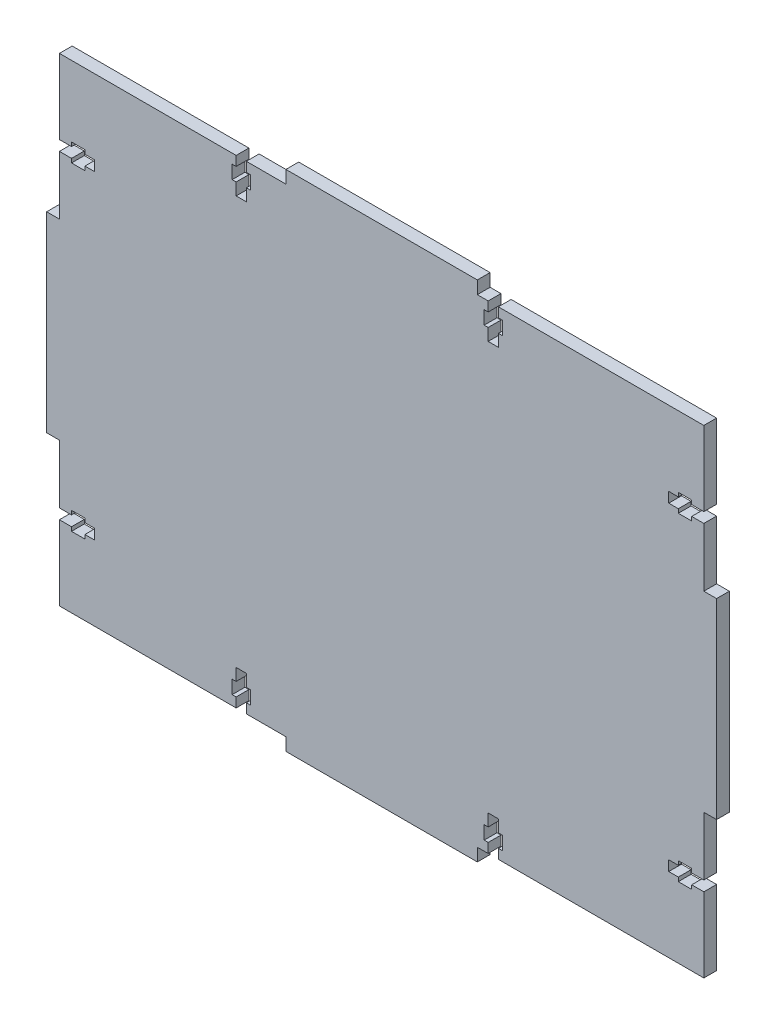
SolidWorks part; units mm, degrees
ref_plane "Plan de face" through (0, 0, 0) normal (0, 0, 1) x (1, 0, 0)
ref_plane "Plan de dessus" through (0, 0, 0) normal (0, 1, 0) x (1, 0, 0)
ref_plane "Plan de droite" through (0, 0, 0) normal (1, 0, 0) x (0, 0, -1)
sketch "Esquisse1" plane through (0, 0, 0) normal (0, 0, 1) x (1, 0, 0)
  line L1 (101, -75) -> (-101, -75)
  line L2 (101, -75) -> (101, 75)
  line L3 (101, 75) -> (-101, 75)
  line L4 (-101, -75) -> (-101, 75)
  line L5 (101, -75) -> (-101, 75) construction
  line L6 (101, 75) -> (-101, -75) construction
  point P0 (0, 0)
  dimension "D1" = 150
  dimension "D2" = 202
extrude "Boss.-Extru.1" add sketch "Esquisse1" along normal blind 4
sketch "Esquisse2" plane through (0, 0, 0) normal (0, 0, -1) x (-1, 0, 0)
  line L0 (-101, -75) -> (-101, 75) construction
  line L1 (-101, 30) -> (-105, 30)
  line L2 (-101, 30) -> (-101, -30)
  line L3 (-101, -30) -> (-105, -30)
  line L4 (-105, 30) -> (-105, -30)
  line L5 (-105, -30) -> (-105, -75) construction
  line L6 (101, 75) -> (101, -75) construction
  line L7 (101, 30) -> (105, 30)
  line L8 (101, 30) -> (101, -30)
  line L9 (101, -30) -> (105, -30)
  line L10 (105, 30) -> (105, -30)
  line L11 (105, 75) -> (105, 30) construction
  line L12 (101, -75) -> (-101, -75) construction
  line L13 (-30, -75) -> (30, -75)
  line L14 (-30, -75) -> (-30, -79)
  line L15 (-30, -79) -> (30, -79)
  line L16 (30, -75) -> (30, -79)
  line L17 (105, -79) -> (30, -79) construction
  line L18 (-101, 75) -> (101, 75) construction
  line L19 (-30, 75) -> (30, 75)
  line L20 (-30, 75) -> (-30, 79)
  line L21 (-30, 79) -> (30, 79)
  line L22 (30, 75) -> (30, 79)
  point P24 (-101, 0)
  point P26 (101, 0)
  point P27 (0, -75)
  dimension "D1" = 60
  dimension "D2" = 60
  dimension "D3" = 60
  dimension "D4" = 60
extrude "Boss.-Extru.2" add sketch "Esquisse2" against normal blind 4
sketch "Esquisse3" plane through (0, 0, 0) normal (0, 0, -1) x (-1, 0, 0)
  line L0 (42.4, 75) -> (45.6, 75)
  line L1 (42.4, 75) -> (42.4, 72)
  line L2 (42.4, 64) -> (45.6, 64)
  line L3 (42.4, 67.8) -> (41.15, 67.8)
  line L4 (46.85, 67.8) -> (45.6, 67.8)
  line L5 (46.85, 67.8) -> (46.85, 72)
  line L6 (46.85, 72) -> (45.6, 72)
  line L7 (41.15, 67.8) -> (41.15, 72)
  line L8 (46.85, 67.8) -> (41.15, 72) construction
  line L9 (46.85, 72) -> (41.15, 67.8) construction
  line L10 (42.4, 72) -> (41.15, 72)
  line L11 (42.4, 67.8) -> (42.4, 64)
  line L12 (45.6, 67.8) -> (45.6, 64)
  line L13 (45.6, 75) -> (45.6, 72)
  line L14 (30, 75) -> (101, 75) construction
  line L15 (45.6, 75) -> (45.6, 79) construction
  line L16 (-36.6, 75) -> (-33.4, 75)
  line L17 (-36.6, 75) -> (-36.6, 72)
  line L18 (-36.6, 64) -> (-33.4, 64)
  line L19 (-36.6, 67.8) -> (-37.85, 67.8)
  line L20 (-32.15, 67.8) -> (-33.4, 67.8)
  line L21 (-32.15, 67.8) -> (-32.15, 72)
  line L22 (-32.15, 72) -> (-33.4, 72)
  line L23 (-37.85, 67.8) -> (-37.85, 72)
  line L24 (-32.15, 67.8) -> (-37.85, 72) construction
  line L25 (-32.15, 72) -> (-37.85, 67.8) construction
  line L26 (-36.6, 72) -> (-37.85, 72)
  line L27 (-36.6, 67.8) -> (-36.6, 64)
  line L28 (-33.4, 67.8) -> (-33.4, 64)
  line L29 (-33.4, 75) -> (-33.4, 72)
  line L30 (-101, 75) -> (-30, 75) construction
  line L31 (-33.4, 75) -> (-33.4, 79) construction
  line L32 (-123.717, 0) -> (130.5234, 0) construction
  line L33 (-32.15, -72) -> (-37.85, -67.8) construction
  line L34 (-32.15, -67.8) -> (-37.85, -72) construction
  line L35 (46.85, -72) -> (41.15, -67.8) construction
  line L36 (46.85, -67.8) -> (41.15, -72) construction
  line L37 (-33.4, -75) -> (-33.4, -72)
  line L38 (-33.4, -67.8) -> (-33.4, -64)
  line L39 (-36.6, -67.8) -> (-36.6, -64)
  line L40 (-36.6, -72) -> (-37.85, -72)
  line L41 (-37.85, -67.8) -> (-37.85, -72)
  line L42 (-32.15, -72) -> (-33.4, -72)
  line L43 (-32.15, -67.8) -> (-32.15, -72)
  line L44 (-32.15, -67.8) -> (-33.4, -67.8)
  line L45 (-36.6, -67.8) -> (-37.85, -67.8)
  line L46 (-36.6, -64) -> (-33.4, -64)
  line L47 (-36.6, -75) -> (-36.6, -72)
  line L48 (-36.6, -75) -> (-33.4, -75)
  line L49 (45.6, -75) -> (45.6, -72)
  line L50 (45.6, -67.8) -> (45.6, -64)
  line L51 (42.4, -67.8) -> (42.4, -64)
  line L52 (42.4, -72) -> (41.15, -72)
  line L53 (41.15, -67.8) -> (41.15, -72)
  line L54 (46.85, -72) -> (45.6, -72)
  line L55 (46.85, -67.8) -> (46.85, -72)
  line L56 (46.85, -67.8) -> (45.6, -67.8)
  line L57 (42.4, -67.8) -> (41.15, -67.8)
  line L58 (42.4, -64) -> (45.6, -64)
  line L59 (42.4, -75) -> (42.4, -72)
  line L60 (42.4, -75) -> (45.6, -75)
  point P4 (44, 69.9)
  point P21 (-35, 69.9)
  point P61 (-35, -69.9)
  point P62 (44, -69.9)
  dimension "D1" = 3.2
  dimension "D2" = 5.7
  dimension "D3" = 4.2
  dimension "D4" = 3
  dimension "D5" = 1.25
  dimension "D6" = 1.25
  dimension "D7" = 1.25
  dimension "D8" = 3.8
  dimension "D9" = 11
  dimension "D10" = 0
  dimension "D11" = 0
  dimension "D12" = 3.2
  dimension "D13" = 5.7
  dimension "D14" = 4.2
  dimension "D15" = 3
  dimension "D16" = 1.25
  dimension "D17" = 1.25
  dimension "D18" = 1.25
  dimension "D19" = 3.8
  dimension "D20" = 11
  dimension "D21" = 0
  dimension "D22" = 0
extrude "Enlèv. mat.-Extru.1" cut sketch "Esquisse3" against normal blind 10
sketch "Esquisse4" plane through (0, 0, 4) normal (0, 0, 1) x (1, 0, 0)
  line L0 (90, 48.4) -> (93, 48.4)
  line L1 (90, 48.4) -> (90, 51.6)
  line L2 (90, 51.6) -> (93, 51.6)
  line L3 (101, 48.4) -> (101, 51.6)
  line L4 (93, 51.6) -> (93, 52.85)
  line L5 (93, 47.15) -> (97.2, 47.15)
  line L6 (93, 47.15) -> (93, 48.4)
  line L7 (93, 52.85) -> (97.2, 52.85)
  line L8 (97.2, 47.15) -> (97.2, 48.4)
  line L9 (97.2, 48.4) -> (101, 48.4)
  line L10 (97.2, 51.6) -> (97.2, 52.85)
  line L11 (97.2, 51.6) -> (101, 51.6)
  line L12 (105, 51.6) -> (101, 51.6) construction
  line L13 (101, 30) -> (101, 75) construction
  line L14 (62.6914, 0) -> (-41.8257, 0) construction
  line L15 (97.2, -51.6) -> (101, -51.6)
  line L16 (97.2, -51.6) -> (97.2, -52.85)
  line L17 (97.2, -48.4) -> (101, -48.4)
  line L18 (97.2, -47.15) -> (97.2, -48.4)
  line L19 (93, -52.85) -> (97.2, -52.85)
  line L20 (93, -47.15) -> (93, -48.4)
  line L21 (93, -47.15) -> (97.2, -47.15)
  line L22 (93, -51.6) -> (93, -52.85)
  line L23 (101, -48.4) -> (101, -51.6)
  line L24 (90, -51.6) -> (93, -51.6)
  line L25 (90, -48.4) -> (90, -51.6)
  line L26 (90, -48.4) -> (93, -48.4)
  line L27 (0, 28.1535) -> (0, -30.8433) construction
  line L28 (-90, -48.4) -> (-93, -48.4)
  line L29 (-90, -48.4) -> (-90, -51.6)
  line L30 (-90, -51.6) -> (-93, -51.6)
  line L31 (-101, -48.4) -> (-101, -51.6)
  line L32 (-93, -51.6) -> (-93, -52.85)
  line L33 (-93, -47.15) -> (-97.2, -47.15)
  line L34 (-93, -47.15) -> (-93, -48.4)
  line L35 (-93, -52.85) -> (-97.2, -52.85)
  line L36 (-97.2, -47.15) -> (-97.2, -48.4)
  line L37 (-97.2, -48.4) -> (-101, -48.4)
  line L38 (-97.2, -51.6) -> (-97.2, -52.85)
  line L39 (-97.2, -51.6) -> (-101, -51.6)
  line L40 (-97.2, 51.6) -> (-101, 51.6)
  line L41 (-97.2, 51.6) -> (-97.2, 52.85)
  line L42 (-97.2, 48.4) -> (-101, 48.4)
  line L43 (-97.2, 47.15) -> (-97.2, 48.4)
  line L44 (-93, 52.85) -> (-97.2, 52.85)
  line L45 (-93, 47.15) -> (-93, 48.4)
  line L46 (-93, 47.15) -> (-97.2, 47.15)
  line L47 (-93, 51.6) -> (-93, 52.85)
  line L48 (-101, 48.4) -> (-101, 51.6)
  line L49 (-90, 51.6) -> (-93, 51.6)
  line L50 (-90, 48.4) -> (-90, 51.6)
  line L51 (-90, 48.4) -> (-93, 48.4)
  dimension "D1" = 11
  dimension "D2" = 3.2
  dimension "D3" = 5.7
  dimension "D4" = 1.25
  dimension "D5" = 4.2
  dimension "D6" = 3
  dimension "D7" = 0
  dimension "D8" = 0
extrude "Enlèv. mat.-Extru.2" cut sketch "Esquisse4" against normal blind 4
